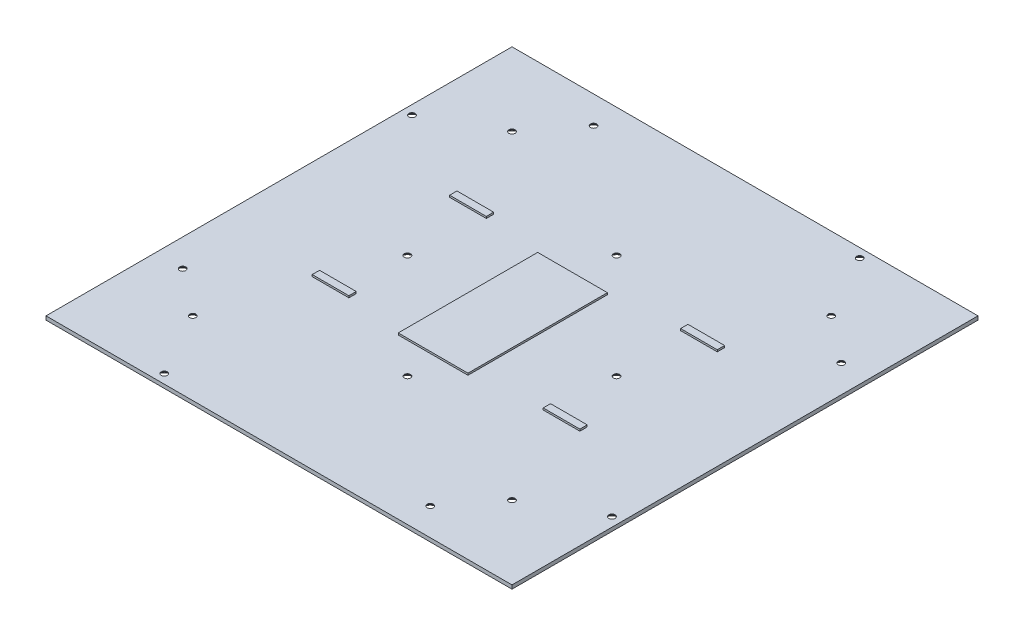
SolidWorks part; units mm, degrees
ref_plane "Front Plane" through (0, 0, 0) normal (0, 0, 1) x (1, 0, 0)
ref_plane "Top Plane" through (0, 0, 0) normal (0, 1, 0) x (1, 0, 0)
ref_plane "Right Plane" through (0, 0, 0) normal (1, 0, 0) x (0, 0, -1)
sketch "Sketch1" plane through (0, 0, 0) normal (0, 1, 0) x (1, 0, 0)
  line L1 (-127, -127) -> (127, -127)
  line L2 (-127, -127) -> (-127, 127)
  line L3 (-127, 127) -> (127, 127)
  line L4 (127, -127) -> (127, 127)
  line L5 (-127, -127) -> (127, 127) construction
  line L6 (-127, 127) -> (127, -127) construction
  point P0 (0, 0)
  dimension "D1" = 254
extrude "Boss-Extrude1" add sketch "Sketch1" along normal mid plane 2.032
sketch "Sketch2" plane through (0, -1.016, 0) normal (0, 1, 0) x (1, 0, 0)
  line L0 (-67.5, -127) -> (-67.5, -122) construction
  line L1 (-127, -127) -> (127, -127) construction
  line L2 (67.5, -127) -> (67.5, -112) construction
  line L3 (-127, 127) -> (-127, -127) construction
  line L4 (127, -127) -> (127, 127) construction
  line L5 (-127, 67.5) -> (-122, 67.5) construction
  line L6 (-127, -67.5) -> (-112, -67.5) construction
  line L7 (67.5, 127) -> (67.5, 122) construction
  line L8 (-67.5, 127) -> (-67.5, 112) construction
  line L9 (127, -67.5) -> (122, -67.5) construction
  line L10 (127, 67.5) -> (112, 67.5) construction
  line L11 (127, 127) -> (-127, 127) construction
  point P25 (0, 0)
  dimension "D1" = 59.5
  dimension "D2" = 59.5
  dimension "D3" = 15
  dimension "D4" = 5
  dimension "D5" = 4
hole_wizard "CSK for M3 Flat Head Machine Screw2" positions "Sketch8" profile "Sketch9" countersink size "M3" standard "ANSI Metric" end condition through all
sketch "Sketch8" plane through (0, -1.016, 0) normal (0, -1, 0) x (-1, 0, 0)
  point P0 (67.5, 112)
  point P3 (122, 67.5)
  point P6 (112, -67.5)
  point P9 (67.5, -122)
  point P12 (-67.5, -112)
  point P15 (-112, 67.5)
  point P18 (-67.5, 122)
  point P21 (-122, -67.5)
sketch "Sketch9" plane through (-67.5, -1.016, -112) normal (1, 0, 0) x (0, 0, -1)
  line L0 (0, 0) -> (0, 2.032)
  line L1 (0, 2.032) -> (1.7, 2.032)
  line L2 (1.7, 2.032) -> (1.7, 1.7)
  line L3 (1.7, 1.7) -> (3.4, 0)
  line L5 (3.4, 0) -> (0, 0)
  line L6 (-1.7, 1.7) -> (-3.4, 0) construction
  line L11 (0, -6.35) -> (0, 107.95) construction
  dimension "Thru Hole Dia." = 3.4
  dimension "Thru Hole Depth" = 2.032
  dimension "Near C'Sink Dia." = 6.8
  dimension "Near C'Sink Angle" = 90
sketch "Sketch10" plane through (0, 1.016, 0) normal (0, 1, 0) x (1, 0, 0)
  line L25 (-107.95, -107.95) -> (107.95, -107.95) construction
  line L26 (-107.95, -107.95) -> (-107.95, 107.95) construction
  line L27 (-107.95, 107.95) -> (107.95, 107.95) construction
  line L28 (107.95, -107.95) -> (107.95, 107.95) construction
  line L29 (-107.95, -107.95) -> (107.95, 107.95) construction
  line L30 (-107.95, 107.95) -> (107.95, -107.95) construction
  line L31 (-72.95, 42.95) -> (-52.95, 42.95)
  line L32 (-72.95, 42.95) -> (-72.95, 38.95)
  line L33 (-72.95, 38.95) -> (-52.95, 38.95)
  line L34 (-52.95, 42.95) -> (-52.95, 38.95)
  line L35 (52.95, 42.95) -> (72.95, 42.95)
  line L36 (52.95, 42.95) -> (52.95, 38.95)
  line L37 (52.95, 38.95) -> (72.95, 38.95)
  line L38 (72.95, 42.95) -> (72.95, 38.95)
  line L39 (-72.95, -31.95) -> (-52.95, -31.95)
  line L40 (-72.95, -31.95) -> (-72.95, -35.95)
  line L41 (-72.95, -35.95) -> (-52.95, -35.95)
  line L42 (-52.95, -31.95) -> (-52.95, -35.95)
  line L43 (52.95, -31.95) -> (72.95, -31.95)
  line L44 (52.95, -31.95) -> (52.95, -35.95)
  line L45 (52.95, -35.95) -> (72.95, -35.95)
  line L46 (72.95, -31.95) -> (72.95, -35.95)
  line L47 (-21.95, 35.95) -> (16.05, 35.95)
  line L48 (-21.95, 35.95) -> (-21.95, -40.05)
  line L49 (-21.95, -40.05) -> (16.05, -40.05)
  line L50 (16.05, 35.95) -> (16.05, -40.05)
  point P0 (0, 0)
  point P25 (0, 0)
  point P26 (0, 0)
  point P27 (0, 0)
  dimension "D1" = 215.9
  dimension "D2" = 76
  dimension "D3" = 38
  dimension "D4" = 86
  dimension "D5" = 72
  dimension "D6" = 35
  dimension "D7" = 65
  dimension "D8" = 20
  dimension "D9" = 4
  dimension "D10" = 72
  dimension "D11" = 35
extrude "Boss-Extrude2" add sketch "Sketch10" along normal blind 1
sketch "Sketch12" plane through (0, -1.016, 0) normal (0, -1, 0) x (1, 0, 0)
  line L0 (-127, -127) -> (-127, 127) construction
  line L1 (-87, -87) -> (87, -87) construction
  line L2 (-87, -87) -> (-87, 87) construction
  line L3 (-87, 87) -> (87, 87) construction
  line L4 (87, -87) -> (87, 87) construction
  line L5 (-87, -87) -> (87, 87) construction
  line L6 (-87, 87) -> (87, -87) construction
  line L7 (-87, 0) -> (0, 0) construction
  line L8 (0, 0) -> (0, 87) construction
  line L9 (87, 0) -> (0, 0) construction
  line L10 (0, 0) -> (0, -87) construction
  line L11 (127, -127) -> (-127, -127) construction
  point P0 (0, 0)
  point P12 (-57, 0)
  point P14 (0, 57)
  point P15 (57, 0)
  point P16 (0, -57)
  point P17 (0, 0)
  point P18 (0, 0)
  point P19 (0, 0)
  point P20 (0, 0)
  point P21 (0, -62.3379)
  point P22 (-58.2786, 0)
  point P23 (64.3562, 0)
  point P24 (0, 63.6385)
  dimension "D1" = 40
  dimension "D2" = 30
  dimension "D3" = 30
  dimension "D4" = 30
  dimension "D5" = 30
  dimension "D6" = 70
hole_wizard "CSK for M3 Flat Head Machine Screw3" positions "3DSketch1" profile "Sketch13" countersink size "M3" standard "ANSI Metric" end condition through all
sketch3d "3DSketch1"
  point P0 (0, -1.016, 57)
  point P3 (57, -1.016, 0)
  point P6 (-57, -1.016, 0)
  point P9 (0, -1.016, -57)
  point P12 (-87, -1.016, -87)
  point P15 (-87, -1.016, 87)
  point P18 (87, -1.016, 87)
  point P21 (87, -1.016, -87)
sketch "Sketch13" plane through (0, -1.016, 57) normal (1, 0, 0) x (0, 0, -1)
  line L0 (0, 0) -> (0, 3.032)
  line L1 (0, 3.032) -> (1.7, 3.032)
  line L2 (1.7, 3.032) -> (1.7, 1.7)
  line L3 (1.7, 1.7) -> (3.4, 0)
  line L5 (3.4, 0) -> (0, 0)
  line L6 (-1.7, 1.7) -> (-3.4, 0) construction
  line L11 (0, -6.35) -> (0, 107.95) construction
  dimension "Thru Hole Dia." = 3.4
  dimension "Thru Hole Depth" = 3.032
  dimension "Near C'Sink Dia." = 6.8
  dimension "Near C'Sink Angle" = 90
equation "\"D2@Sketch2\"=\"D1@Sketch2\""
equation "\"D3@Sketch12\"=\"D2@Sketch12\""
equation "\"D4@Sketch12\"=\"D2@Sketch12\""
equation "\"D5@Sketch12\"=\"D2@Sketch12\""
equation "\"D10@Sketch10\"=\"D5@Sketch10\""
equation "\"D11@Sketch10\"=\"D6@Sketch10\""
